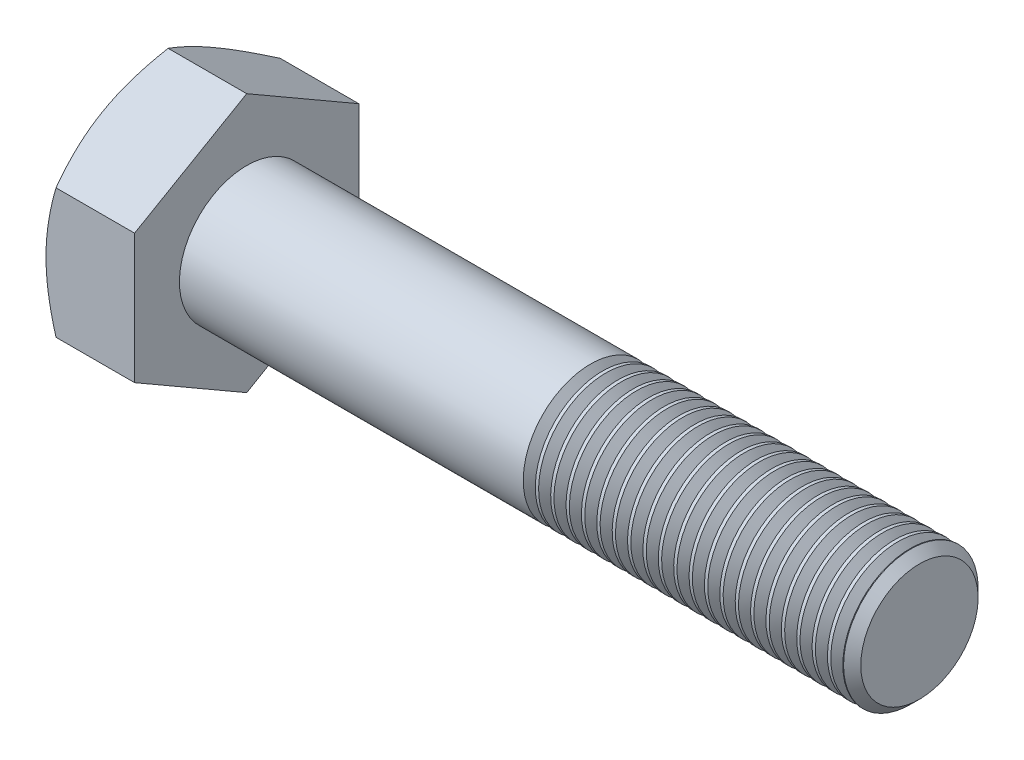
SolidWorks part; units mm, degrees
extrude "BaseHead" add sketch "Sketch1" along normal blind 19.75
sketch "Sketch1" plane through (0, 0, 0) normal (1, 0, 0) x (0, 0, -1)
  line L0 (25, 14.4338) -> (25, -14.4338)
  line L1 (-25, 14.4338) -> (-25, -14.4338)
  line L2 (25, -14.4338) -> (0, -28.8675)
  line L3 (0, -28.8675) -> (-25, -14.4338)
  line L4 (25, 14.4338) -> (0, 28.8675)
  line L5 (0, 28.8675) -> (-25, 14.4338)
  dimension "Width_flats" = 50
  dimension "D2" = 120
  dimension "D3" = 25
  dimension "D4" = 25
  dimension "D5" = 25
material "A286 Demir Tabanlı Süperalaşım"
ref_plane "Plane1" through (0, 0, 0) normal (0, 0, 1) x (1, 0, 0)
ref_plane "Plane2" through (0, 0, 0) normal (0, 1, 0) x (1, 0, 0)
ref_plane "Plane3" through (0, 0, 0) normal (1, 0, 0) x (0, 0, -1)
sketch "BodySke" plane through (0, 0, 0) normal (0, 0, 1) x (1, 0, 0)
  line L0 (0, 14.4338) -> (0, -14.4338) construction
  line L1 (0, 0) -> (169.75, 0)
  line L2 (0, 0) -> (0, 15)
  line L3 (0, 15) -> (167.829, 15)
  line L4 (169.75, 0) -> (169.75, 13.079)
  line L5 (19.75, 28.8675) -> (19.75, 14.4338) construction
  line L6 (169.75, 13.079) -> (167.829, 15)
  line L7 (0, 0) -> (96.52, 0) construction
  line L8 (169.75, -13.079) -> (167.829, -15) construction
  line L9 (0, -15) -> (167.829, -15) construction
  line L10 (23.25, 15.24) -> (23.25, -1.27) construction
  line L11 (97.75, 15.24) -> (97.75, -1.27) construction
  line L12 (19.75, 14.4338) -> (19.75, -14.4338) construction
  dimension "Diameter" = 30
revolve "BaseBody" add sketch "BodySke"
cosmetic thread "ThreadCosmetic" [suppressed]
fillet "HeadFillet" [suppressed] radius 1
sketch "Sketch3" plane through (0, 0, 0) normal (0, 0, 1) x (1, 0, 0)
  line L0 (0, 25) -> (5.1197, 33.8675)
  line L1 (0, 28.8675) -> (0, 14.4338) construction
  line L2 (5.1197, 33.8675) -> (5.1197, 38.8675)
  line L3 (5.1197, 38.8675) -> (-10, 38.8675)
  line L4 (-10, 38.8675) -> (-10, 25)
  line L5 (-10, 25) -> (0, 25)
  line L6 (0, 0) -> (99.06, 0) construction
  line L7 (19.75, 28.8675) -> (0, 28.8675) construction
  dimension "D1" = 25
  dimension "D2" = 5
  dimension "D3" = 10
  dimension "D4" = 5
  dimension "Head_ch_ang" = 30
revolve "HeadChamfer" cut sketch "Sketch3" angle 360 about L6
sketch "ThdSchSke" plane through (0, 0, 0) normal (0, 0, 1) x (1, 0, 0)
  line L0 (97.75, -13.079) -> (96.4049, -15)
  line L1 (97.75, -13.079) -> (99.0951, -15)
  line L2 (99.0951, -15) -> (99.0951, -18.75)
  line L3 (-3.175, 0) -> (5.1513, 0) construction
  line L5 (99.0951, -18.75) -> (96.4049, -18.75)
  line L6 (96.4049, -18.75) -> (96.4049, -15)
  dimension "Thread_minor" = 26.158
  dimension "Diameter" = 30
  dimension "Start" = 97.75
revolve "ThreadSchematic" cut sketch "ThdSchSke" angle 360 about L3
pattern_linear "ThdSchPat" count 21 spacing 3.4286 along (1, 0, 0) of "ThreadSchematic"
equation "\"D3@Sketch1\" = \"Width_flats@Sketch1\" / 2"
equation "\"D4@Sketch1\" = \"D3@Sketch1\""
equation "\"D5@Sketch1\" = \"D4@Sketch1\""
equation "\"Thread_minor@ThreadCosmetic\" = \"Minor_dia@BodySke\""
equation "\"D1@Sketch3\" = \"Width_flats@Sketch1\" / 2"
equation "' \"D1@Sketch4\" = \"Width_flats@Sketch1\""
equation "\"Thread_length@ThreadCosmetic\" = ((sgn( (\"Length@BodySke\" - \"Advance@BodySke\" ) - \"Thread_nom@BodySke\" )-1)*( (\"Length@BodySke\" - \"Advance@BodySke\" ) - \"Thread_nom@BodySke\" ))/-2+ \"Thread_nom@BodySke\""
equation "\"Thread_minor@ThdSchSke\" = \"Minor_dia@BodySke\""
equation "\"Diameter@ThdSchSke\" = \"Diameter@BodySke\""
equation "\"Overcut@ThdSchSke\" = \"Diameter@BodySke\" * 1.25"
equation "\"Start@ThdSchSke\" = \"Head_ht@BaseHead\" + \"Length@BodySke\" - \"Thread_length@ThreadCosmetic\"  '---Non-countersunk---"
equation "\"Num_threads@ThdSchPat\" = int( \"Thread_length@ThreadCosmetic\" / \"Advance@BodySke\" + 0.999 )  + 1"
equation "\"Advance@ThdSchPat\" = \"Thread_length@ThreadCosmetic\" /  (\"Num_threads@ThdSchPat\" - 1) 'relax it"
equation "\"Num_threads@ThdSchPat\" = \"Num_threads@ThdSchPat\" - sgn( \"Num_threads@ThdSchPat\" - 1) '---chamfered tips only---"
